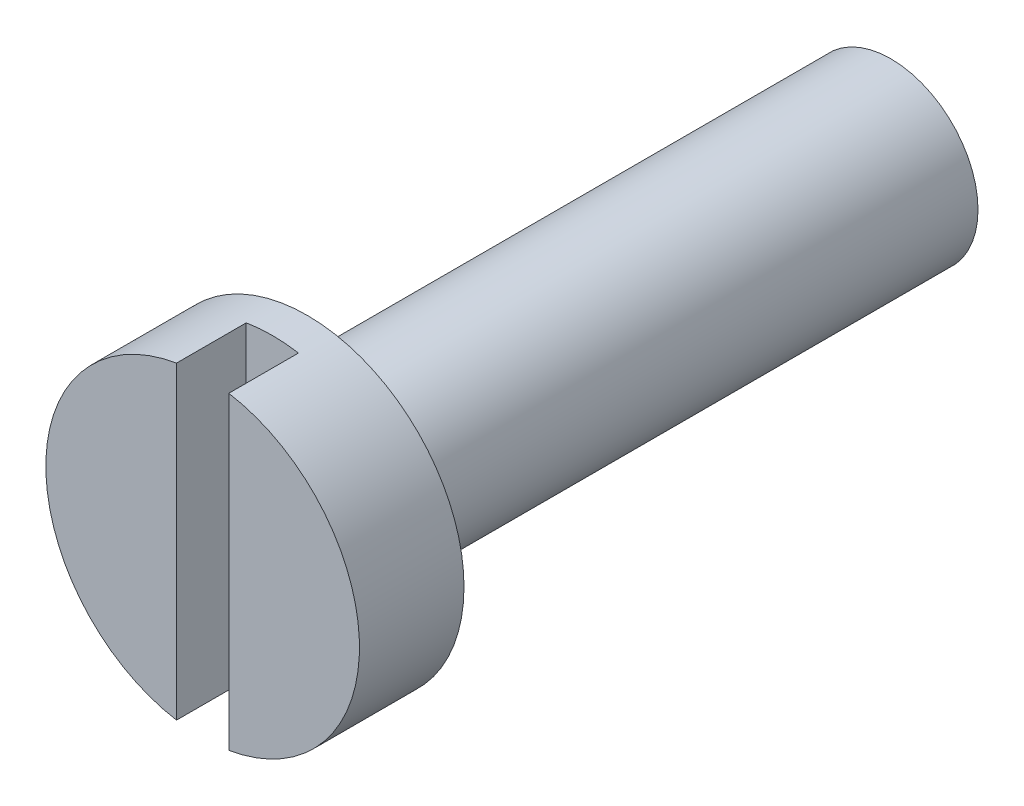
SolidWorks part; units mm, degrees
ref_plane "前视基准面" through (0, 0, 0) normal (0, 0, 1) x (1, 0, 0)
ref_plane "上视基准面" through (0, 0, 0) normal (0, 1, 0) x (1, 0, 0)
ref_plane "右视基准面" through (0, 0, 0) normal (1, 0, 0) x (0, 0, -1)
sketch "草图1" plane through (0, 0, 0) normal (0, 0, 1) x (1, 0, 0)
  circle A0 centre (0, 0) radius 2.5
  dimension "D1" = 5
extrude "凸台-拉伸1" add sketch "草图1" along normal blind 16.75
cosmetic thread "装饰螺纹线2" parameters "D1"=10, "D2"=4.134
sketch "草图2" plane through (0, 0, 16.75) normal (0, 0, 1) x (1, 0, 0)
  circle A0 centre (0, 0) radius 4.5
  dimension "D1" = 9
extrude "凸台-拉伸2" add sketch "草图2" along normal blind 3
sketch "草图4" plane through (0, 0, 19.75) normal (0, 0, 1) x (1, 0, 0)
  line L1 (-0.75, 5.4684) -> (0.75, 5.4684)
  line L2 (-0.75, 5.4684) -> (-0.75, -5.4684)
  line L3 (-0.75, -5.4684) -> (0.75, -5.4684)
  line L4 (0.75, 5.4684) -> (0.75, -5.4684)
  line L5 (-0.75, 5.4684) -> (0.75, -5.4684) construction
  line L6 (-0.75, -5.4684) -> (0.75, 5.4684) construction
  point P0 (0, 0)
  dimension "D1" = 1.5
extrude "切除-拉伸1" cut sketch "草图4" against normal blind 2
sketch "草图5" plane through (0, 0, 0) normal (0, 0, -1) x (-1, 0, 0)
  point P0 (0, 0)
  point P1 (-8.9921, 4.042)
hole_wizard "M3 螺纹孔的螺纹孔钻头1" positions "草图6" profile "草图8" hole size "M3" standard "GB"
sketch "草图6" plane through (0, 0, 0) normal (0, 0, -1) x (-1, 0, 0)
  point P0 (0, 0)
sketch "草图8" plane through (0, 0, 0) normal (1, 0, 0) x (0, 1, 0)
  line L0 (0, 0) -> (0, 10.7511)
  line L1 (0, 10.7511) -> (1.25, 10)
  line L2 (1.25, 10) -> (1.25, 0)
  line L5 (1.25, 0) -> (0, 0)
  line L10 (0, 10.7511) -> (-1.25, 10) construction
  line L11 (0, -6.35) -> (0, 107.95) construction
  dimension "孔直径" = 2.5
  dimension "孔深度" = 10
  dimension "导头角度" = 118
